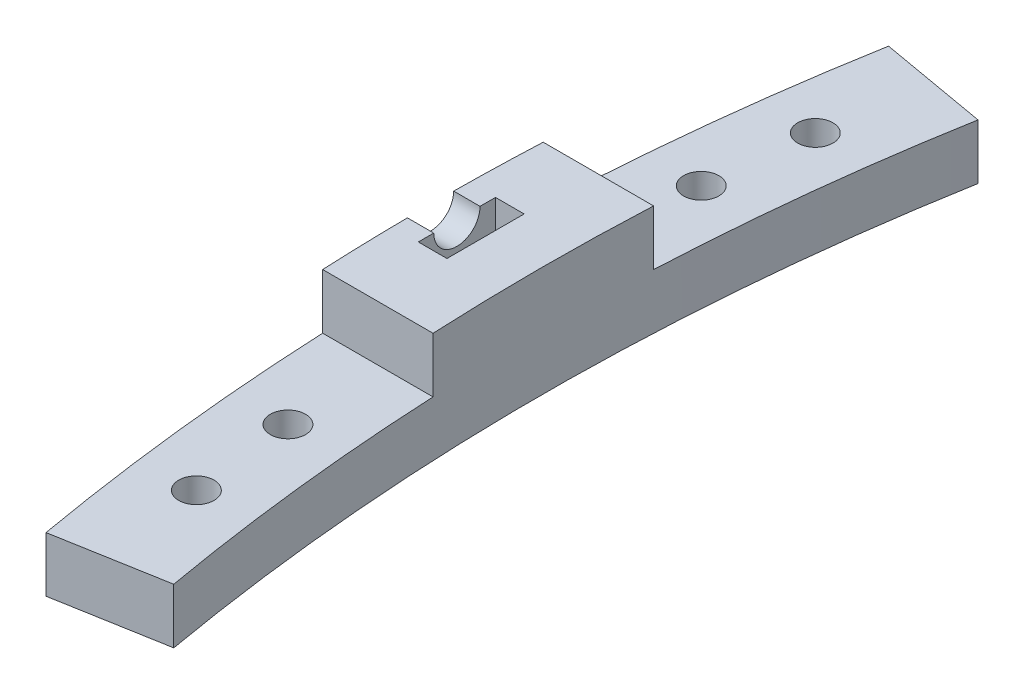
SolidWorks part; units mm, degrees
ref_plane "Front Plane" through (0, 0, 0) normal (0, 0, 1) x (1, 0, 0)
ref_plane "Top Plane" through (0, 0, 0) normal (0, 1, 0) x (1, 0, 0)
ref_plane "Right Plane" through (0, 0, 0) normal (1, 0, 0) x (0, 0, -1)
sketch "Sketch1" plane through (0, 0, 0) normal (0, 1, 0) x (1, 0, 0)
  line L0 (0, 0) -> (-216.6577, -38.2026) construction
  line L1 (0, 0) -> (-216.6577, 38.2026) construction
  line L2 (0, 0) -> (-215, 0) construction
  line L3 (-216.6577, 38.2026) -> (-206.8096, 36.4661)
  line L4 (-206.8096, -36.4661) -> (-216.6577, -38.2026)
  arc A0 (-216.6577, 38.2026) -> (-216.6577, -38.2026) centre (0, 0) ccw
  arc A1 (-206.8096, 36.4661) -> (-206.8096, -36.4661) centre (0, 0) ccw
  arc A2 (-211.7337, -37.3344) -> (-211.7337, 37.3344) centre (0, 0) cw construction
  dimension "D1" = 220
  dimension "D2" = 210
  dimension "D3" = 5
  dimension "D4" = 20
extrude "Boss-Extrude1" add sketch "Sketch1" along normal blind 5
sketch "Sketch2" [suppressed] plane through (0, 7.5, 0) normal (0, 1, 0) x (1, 0, 0)
  line L2 (0, 0) -> (-215, 0) construction
  line L3 (0, 0) -> (-219.1197, -38.6367) construction
  line L4 (0, 0) -> (-219.1197, 38.6367) construction
  line L5 (0, 0) -> (-210, 0) construction
  line L6 (0, 0) -> (-219.1197, -38.6367) construction
  line L7 (0, 0) -> (-219.1197, 38.6367) construction
  line L8 (0, 10) -> (-222.2752, 10) construction
  line L9 (0, 10) -> (0, -10) construction
  line L10 (0, -10) -> (-222.2752, -10) construction
  line L11 (-216.6577, 38.2026) -> (-206.8096, 36.4661)
  line L12 (-216.6577, -38.2026) -> (-206.8096, -36.4661)
  line L13 (-219.7726, -10) -> (-209.7618, -10)
  line L14 (-209.7618, 10) -> (-219.7726, 10)
  arc A0 (-216.6577, 38.2026) -> (-216.6577, -38.2026) centre (0, 0) ccw construction
  arc A1 (-206.8096, 36.4661) -> (-206.8096, -36.4661) centre (0, 0) ccw construction
  arc A2 (-216.6577, 38.2026) -> (-216.6577, -38.2026) centre (0, 0) ccw
  arc A3 (-206.8096, 36.4661) -> (-206.8096, -36.4661) centre (0, 0) ccw
  arc A4 (-219.1197, 38.6367) -> (-219.1197, -38.6367) centre (0, 0) ccw construction
  line M2 (-219.1197, -38.6367) -> (-204.3476, -36.032)
  line M4 (-204.3476, 36.032) -> (-219.1197, 38.6367)
  dimension "D1" = 20
extrude "Cut-Extrude1" [suppressed] cut sketch "Sketch2" against normal blind 1.5 contours A3 A2 L14 M4 | A3 L13 A2 M2
ref_plane "Plane1" through (-215, 0, 0) normal (1, 0, 0) x (0, 0, -1)
sketch "Sketch6" plane through (0, 0, 0) normal (0, -1, 0) x (1, 0, 0)
  line L0 (0, 0) -> (-214.1819, 18.7385) construction
  line L1 (0, 0) -> (-215, 0) construction
  line L2 (0, 0) -> (-215, 0) construction
  line L3 (0, 0) -> (-214.1819, -18.7385) construction
  line L4 (0, 0) -> (-213.1606, 28.0631) construction
  line L5 (0, 0) -> (-213.1606, -28.0631) construction
  arc A0 (-211.7337, 37.3344) -> (-211.7337, -37.3344) centre (0, 0) ccw construction
  dimension "D1" = 5
  dimension "D2" = 7.5
hole_wizard "Ø3.2 (3.2) Diameter Hole1" positions "Sketch7" profile "Sketch8" hole size "Ø3.2" standard "ISO" end condition through all
sketch "Sketch7" plane through (0, 0, 0) normal (0, -1, 0) x (-1, 0, 0)
  point P0 (214.1819, -18.7385)
  point P3 (214.1819, 18.7385)
  point P6 (213.1606, -28.0631)
  point P9 (213.1606, 28.0631)
sketch "Sketch8" plane through (-214.1819, 0, 18.7385) normal (1, 0, 0) x (0, 0, -1)
  line L0 (0, 0) -> (0, 5)
  line L1 (0, 5) -> (1.6, 5)
  line L2 (1.6, 5) -> (1.6, 0)
  line L5 (1.6, 0) -> (0, 0)
  line L11 (0, -6.35) -> (0, 107.95) construction
  dimension "Thru Hole Dia." = 3.2
  dimension "Thru Hole Depth" = 5
sketch "Sketch9" plane through (0, 5, 0) normal (0, 1, 0) x (1, 0, 0)
  line L0 (0, 0) -> (-215, 0) construction
  line L1 (0, 0) -> (-215, 0) construction
  line L2 (0, 10) -> (0, -10) construction
  line L3 (-219.7726, 10) -> (-209.7618, 10)
  line L4 (-219.7726, -10) -> (-209.7618, -10)
  arc A0 (-216.6577, 38.2026) -> (-216.6577, -38.2026) centre (0, 0) ccw construction
  arc A1 (-206.8096, 36.4661) -> (-206.8096, -36.4661) centre (0, 0) ccw construction
  arc A2 (-209.7618, 10) -> (-209.7618, -10) centre (0, 0) ccw
  arc A3 (-219.7726, 10) -> (-219.7726, -10) centre (0, 0) ccw
  dimension "D1" = 20
extrude "Boss-Extrude2" add sketch "Sketch9" along normal blind 5
ref_plane "Plane2" through (-215, 0, 0) normal (-1, 0, 0) x (0, 0, 1)
sketch "Sketch10" plane through (-215, 0, 0) normal (-1, 0, 0) x (0, 0, 1)
  line L0 (10, 10) -> (-10, 10) construction
  line L1 (-3.5, 13.5) -> (3.5, 13.5)
  line L2 (-3.5, 13.5) -> (-3.5, 6.5)
  line L3 (-3.5, 6.5) -> (3.5, 6.5)
  line L4 (3.5, 13.5) -> (3.5, 6.5)
  line L5 (-3.5, 13.5) -> (3.5, 6.5) construction
  line L6 (-3.5, 6.5) -> (3.5, 13.5) construction
  point P0 (0, 10)
  dimension "D1" = 7
  dimension "D2" = 7
extrude "Cut-Extrude2" cut sketch "Sketch10" along normal blind 2.6
sketch "Sketch11" plane through (-215, 0, 0) normal (-1, 0, 0) x (0, 0, 1)
  line L0 (10, 10) -> (-10, 10) construction
  circle A0 centre (0, 10) radius 2.1
  dimension "D1" = 4.2
extrude "Cut-Extrude3" cut sketch "Sketch11" along normal through all
